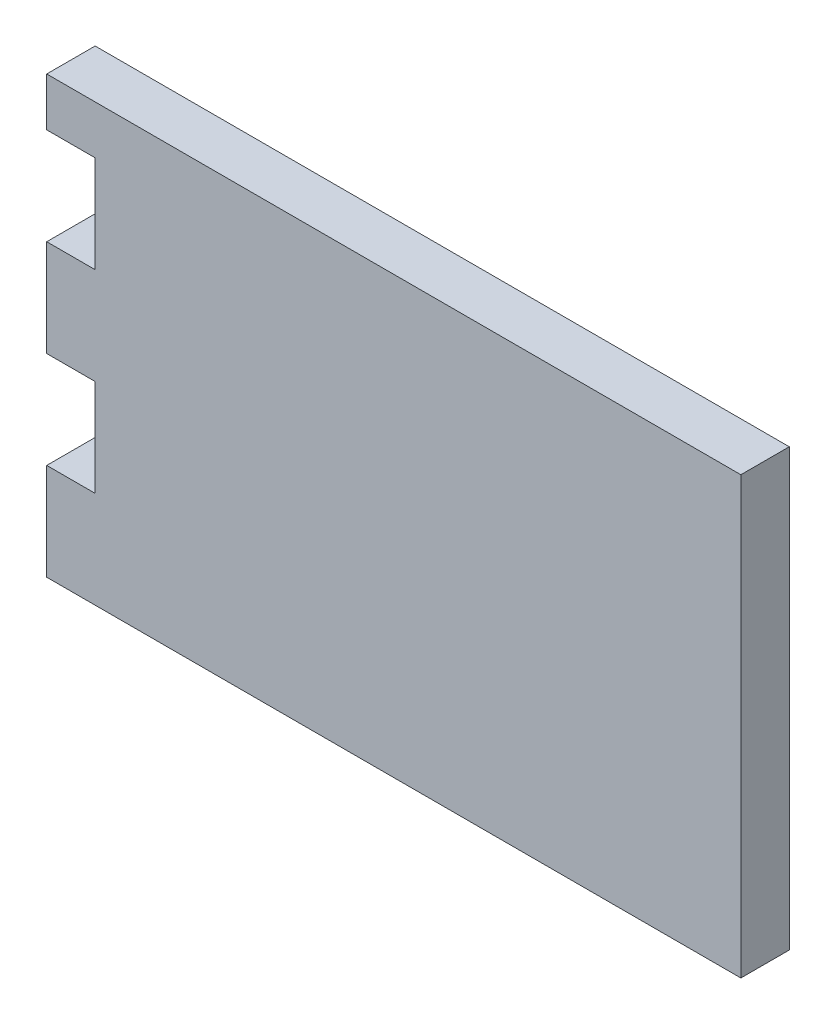
SolidWorks part; units mm, degrees
material "Pine"
ref_plane "Front Plane" through (0, 0, 0) normal (0, 0, 1) x (1, 0, 0)
ref_plane "Top Plane" through (0, 0, 0) normal (0, 1, 0) x (1, 0, 0)
ref_plane "Right Plane" through (0, 0, 0) normal (1, 0, 0) x (0, 0, -1)
sketch "Sketch1" plane through (0, 0, 0) normal (0, 0, 1) x (1, 0, 0)
  line L0 (0, -30) -> (0, -42)
  line L5 (0, 0) -> (86, 0)
  line L6 (0, 0) -> (0, -54)
  line L7 (0, -54) -> (86, -54)
  line L8 (86, 0) -> (86, -54)
  line L9 (0, -54) -> (6, -54)
  line L10 (0, -54) -> (0, -66)
  line L11 (0, -66) -> (6, -66)
  line L12 (6, -54) -> (6, -66)
  line L13 (0, -30) -> (6, -30)
  line L14 (6, -30) -> (6, -42)
  line L15 (0, -42) -> (6, -42)
  line L16 (0, -6) -> (0, -18)
  line L17 (0, -6) -> (6, -6)
  line L18 (6, -6) -> (6, -18)
  line L19 (0, -18) -> (6, -18)
  dimension "D1" = 54
  dimension "D2" = 86
  dimension "D3" = 6
  dimension "D4" = 12
  dimension "D5" = 3
extrude "Boss-Extrude1" add sketch "Sketch1" along normal blind 6 contours L6 L19 L18 L17 L15 L14 L13 L11 L12 L7 L8 L5
